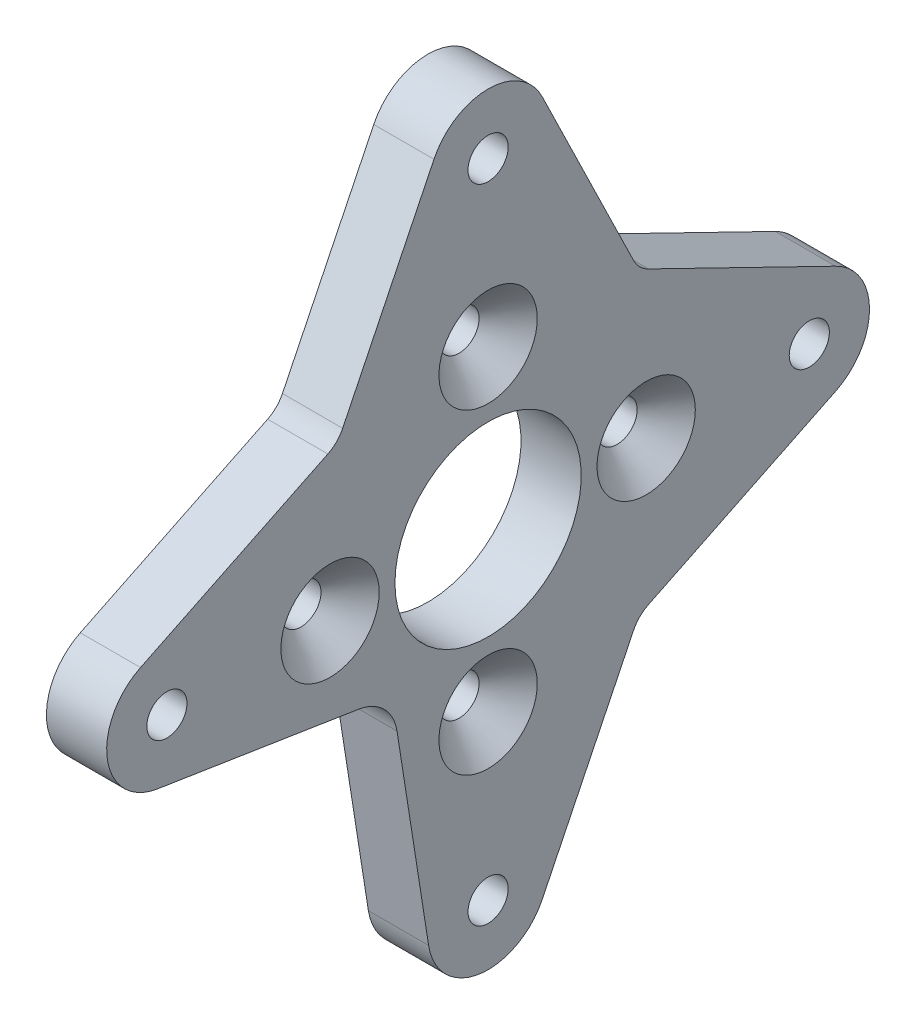
SolidWorks part; units mm, degrees
ref_plane "Front Plane" through (0, 0, 0) normal (0, 0, 1) x (1, 0, 0)
ref_plane "Top Plane" through (0, 0, 0) normal (0, 1, 0) x (1, 0, 0)
ref_plane "Right Plane" through (0, 0, 0) normal (1, 0, 0) x (0, 0, -1)
sketch "Sketch1" plane through (0, 0, 0) normal (1, 0, 0) x (0, 0, -1)
  line L0 (4.2813, 27.4861) -> (11.5, 12.6708)
  line L1 (0, 25.4) -> (0, 0) construction
  line L2 (-4.2813, 27.4861) -> (-11.5, 12.6708)
  line L3 (27.4861, 4.2813) -> (12.6708, 11.5)
  line L4 (27.4861, -4.2813) -> (12.6708, -11.5)
  line L5 (4.2813, -27.4861) -> (11.5, -12.6708)
  line L6 (-4.705, -26.138) -> (-7.2031, -10.2115)
  line L7 (-26.138, -4.705) -> (-10.2115, -7.2031)
  line L8 (-27.4861, 4.2813) -> (-12.6708, 11.5)
  circle A0 centre (0, 0) radius 7.366
  circle A1 centre (0, 25.4) radius 1.5875
  circle A2 centre (0, 12.5) radius 1.5875
  arc A3 (4.2813, 27.4861) -> (-4.2813, 27.4861) centre (0, 25.4) ccw
  arc A4 (12.6708, -11.5) -> (11.5, -12.6708) centre (13.7834, -13.7834) ccw
  circle A5 centre (12.5, 0) radius 1.5875
  circle A6 centre (25.4, 0) radius 1.5875
  arc A7 (27.4861, -4.2813) -> (27.4861, 4.2813) centre (25.4, 0) ccw
  circle A8 centre (0, -12.5) radius 1.5875
  circle A9 centre (0, -25.4) radius 1.5875
  arc A10 (-4.705, -26.138) -> (4.2813, -27.4861) centre (0, -25.4) ccw
  circle A11 centre (-12.5, 0) radius 1.5875
  circle A12 centre (-25.4, 0) radius 1.5875
  arc A13 (-27.4861, 4.2813) -> (-26.138, -4.705) centre (-25.4, 0) ccw
  arc A14 (11.5, 12.6708) -> (12.6708, 11.5) centre (13.7834, 13.7834) ccw
  arc A15 (-12.6708, 11.5) -> (-11.5, 12.6708) centre (-13.7834, 13.7834) ccw
  arc A16 (-7.2031, -10.2115) -> (-10.2115, -7.2031) centre (-10.7712, -10.7712) ccw
  point P22 (11.8836, 11.8836)
  point P31 (-11.8836, 11.8836)
  dimension "D1" = 9.525
  dimension "D3" = 3.175
  dimension "D5" = 3.175
  dimension "D6" = 25.4
  dimension "D4" = 2.54
  dimension "D2" = 12.5
extrude "Boss-Extrude1" add sketch "Sketch1" along normal blind 4.7625
chamfer "Chamfer1" distance 2.3 angle 45 4 edges at (4.7625, 12.5, -1.5875) (4.7625, 0, -14.0875) (4.7625, -12.5, -1.5875) (4.7625, 0, 10.9125)
